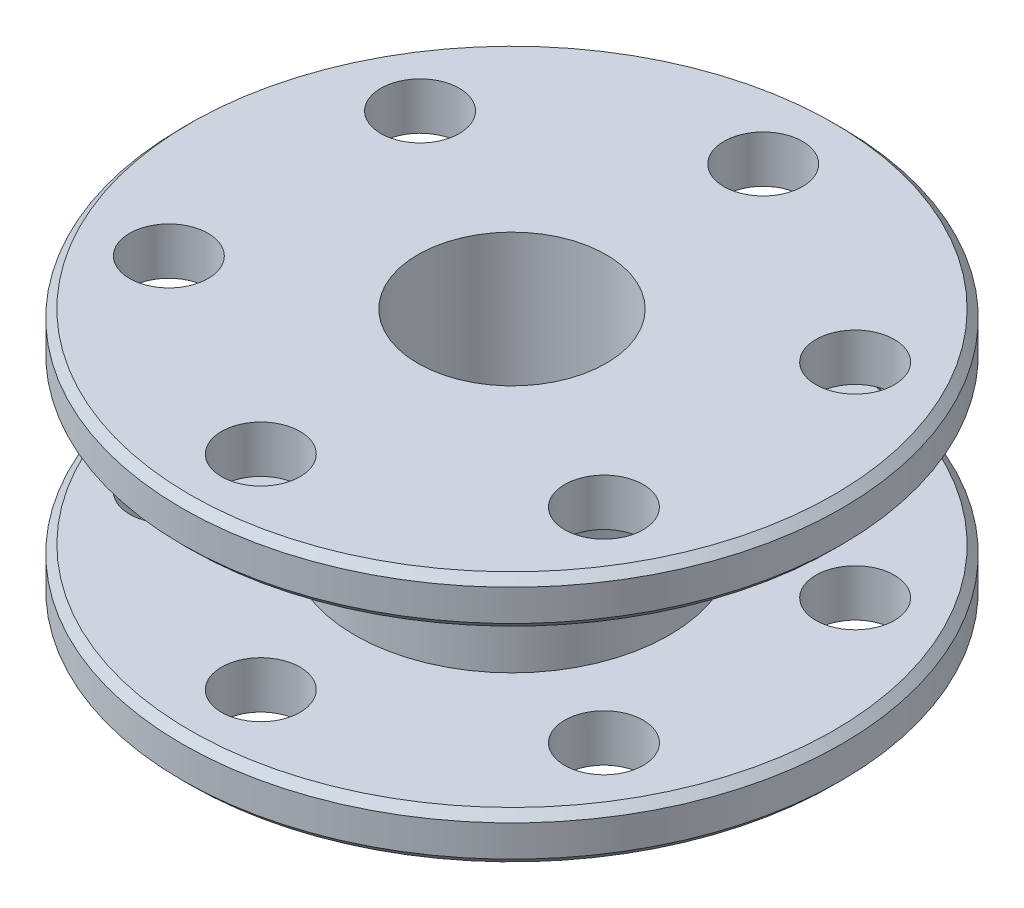
SolidWorks part; units mm, degrees
ref_plane "Front Plane" through (0, 0, 0) normal (0, 0, 1) x (1, 0, 0)
ref_plane "Top Plane" through (0, 0, 0) normal (0, 1, 0) x (1, 0, 0)
ref_plane "Right Plane" through (0, 0, 0) normal (1, 0, 0) x (0, 0, -1)
sketch "Sketch1" plane through (0, 0, 0) normal (0, 1, 0) x (1, 0, 0)
  circle A0 centre (0, 0) radius 21
  circle A1 centre (0, 0) radius 6
  circle A2 centre (0, 0) radius 16 construction
  circle A3 centre (0, 16) radius 2.5
  circle A4 centre (13.8564, 8) radius 2.5
  circle A5 centre (13.8564, -8) radius 2.5
  circle A6 centre (0, -16) radius 2.5
  circle A7 centre (-13.8564, -8) radius 2.5
  circle A8 centre (-13.8564, 8) radius 2.5
  point P19 (0, 0)
  dimension "D1" = 6
extrude "Boss-Extrude1" add sketch "Sketch1" along normal blind 16
sketch "Sketch2" plane through (0, 0, 0) normal (1, 0, 0) x (0, 0, -1)
  line L0 (0, 0) -> (0, 18.556) construction
  line L1 (21, 16) -> (-21, 16) construction
  line L2 (10, 13) -> (21.8726, 13)
  line L3 (10, 13) -> (10, 3)
  line L4 (10, 3) -> (21.8726, 3)
  line L5 (21.8726, 13) -> (21.8726, 3)
  line L6 (-21, 0) -> (21, 0) construction
  dimension "D1" = 10
  dimension "D2" = 3
  dimension "D3" = 3
revolve "Cut-Revolve1" cut sketch "Sketch2" angle 360 about L0
chamfer "Chamfer2" distance 0.5 angle 45 4 edges at (0, 0, 21) (0, 3, -21) (0, 16, 21) (0, 13, 21)
